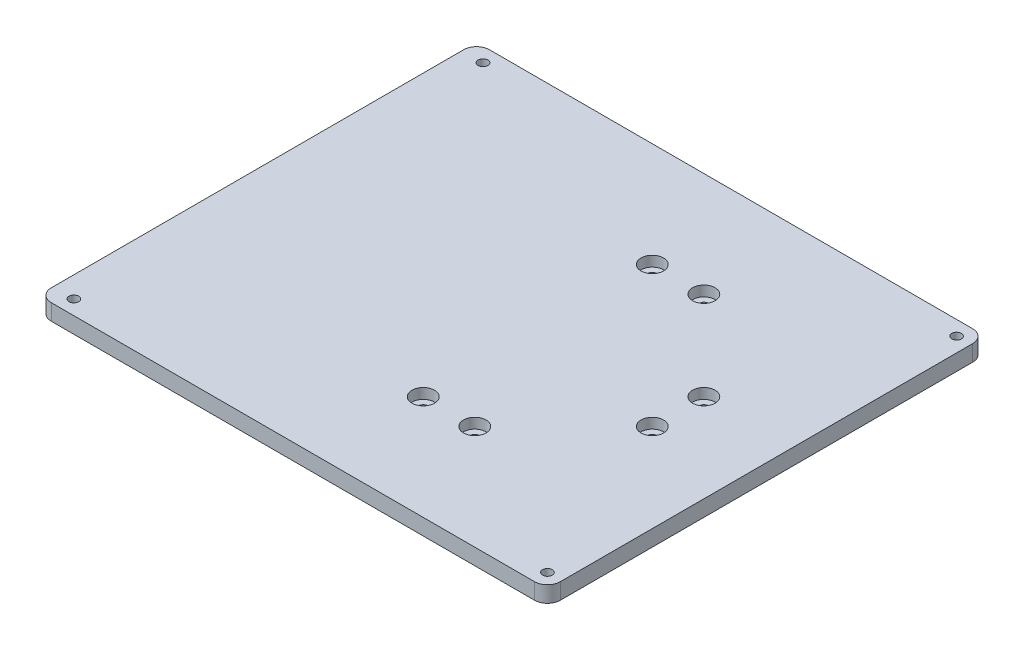
SolidWorks part; units mm, degrees
ref_plane "Front Plane" through (0, 0, 0) normal (0, 0, 1) x (1, 0, 0)
ref_plane "Top Plane" through (0, 0, 0) normal (0, 1, 0) x (1, 0, 0)
ref_plane "Right Plane" through (0, 0, 0) normal (1, 0, 0) x (0, 0, -1)
sketch "Sketch8" plane through (0, 0, 0) normal (0, 1, 0) x (1, 0, 0)
  line L0 (79, 0) -> (65.8191, 0) construction
  line L1 (-79, 68) -> (79, 68)
  line L2 (-79, 68) -> (-79, -68)
  line L3 (-79, -68) -> (79, -68)
  line L4 (79, 68) -> (79, -68)
  circle A0 centre (74.5, 63.5) radius 1.5
  circle A1 centre (-72.5, 63.5) radius 1.5
  circle A2 centre (-72.5, -63.5) radius 1.5
  circle A3 centre (74.5, -63.5) radius 1.5
  point P0 (0, 0)
  dimension "D3" = 3
  dimension "D4" = 4.5
  dimension "D5" = 4.5
  dimension "D6" = 4.5
  dimension "D7" = 6.5
  dimension "D1" = 136
  dimension "D2" = 158
extrude "Boss-Extrude4" add sketch "Sketch8" along normal blind 5
fillet "Fillet2" radius 4 4 edges at (-79, 2.5, 68) (-79, 2.5, -68) (79, 2.5, -68) (79, 2.5, 68)
sketch "Sketch10" plane through (0, 5, 0) normal (0, 1, 0) x (1, 0, 0)
  line L1 (16, 0) -> (16, 35.55) construction
  line L2 (16, 0) -> (51.55, 0) construction
  line L3 (51.55, 0) -> (51.55, 8) construction
  line L5 (79, -64) -> (79, 64) construction
  line L6 (51.55, 0) -> (51.55, -8) construction
  circle A2 centre (24, 35.55) radius 1.5
  circle A3 centre (24, -35.55) radius 1.5
  circle A4 centre (8, -35.55) radius 1.5
  circle A5 centre (8, 35.55) radius 1.5
  circle A10 centre (51.55, -8) radius 1.5
  circle A11 centre (51.55, 8) radius 1.5
  point P2 (16, 0)
  dimension "D1" = 35.55
  dimension "D2" = 3
  dimension "D3" = 8
  dimension "D6" = 63
extrude "Cut-Extrude5" cut sketch "Sketch10" against normal blind 5
sketch "Sketch11" plane through (0, 5, 0) normal (0, 1, 0) x (1, 0, 0)
  circle A0 centre (24, 35.55) radius 3.5
  circle A1 centre (8, 35.55) radius 3.5
  circle A2 centre (51.55, 8) radius 3.5
  circle A3 centre (51.55, -8) radius 3.5
  circle A4 centre (24, -35.55) radius 3.5
  circle A5 centre (8, -35.55) radius 3.5
  dimension "D1" = 7
extrude "Cut-Extrude6" cut sketch "Sketch11" against normal blind 3.2
